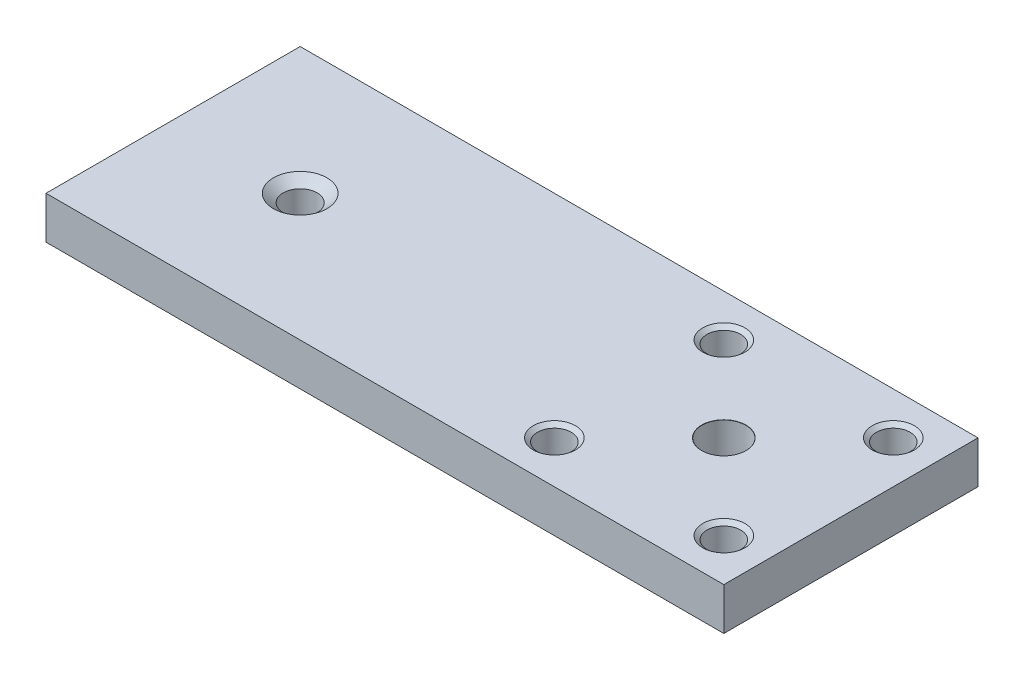
SolidWorks part; units mm, degrees
material "6061 Alloy"
ref_plane "Front" through (0, 0, 0) normal (0, 0, 1) x (1, 0, 0)
ref_plane "Top" through (0, 0, 0) normal (0, 1, 0) x (1, 0, 0)
ref_plane "Right" through (0, 0, 0) normal (1, 0, 0) x (0, 0, -1)
sketch "Sketch1" plane through (0, 0, 0) normal (0, 1, 0) x (1, 0, 0)
  line L1 (0, 0) -> (101.6, 0)
  line L2 (0, 0) -> (0, 38.1)
  line L3 (0, 38.1) -> (101.6, 38.1)
  line L4 (101.6, 0) -> (101.6, 38.1)
  dimension "D1" = 101.6
  dimension "D2" = 38.1
extrude "Boss-Extrude1" add sketch "Sketch1" along normal blind 6.35
hole_wizard "1/4-20 Tapped Hole1" positions "Sketch2" profile "Sketch3" tap size "1/4-20" standard "ANSI Inch" end condition through all
sketch "Sketch2" plane through (0, 6.35, 0) normal (0, 1, 0) x (1, 0, 0)
  line L0 (0, -50) -> (0, 50) construction
  line L1 (19.05, 19.05) -> (0, 19.05) construction
  line L3 (0, 38.1) -> (0, 0) construction
  point P0 (19.05, 19.05)
  dimension "D1" = 19.05
sketch "Sketch3" plane through (19.05, 6.35, -19.05) normal (1, 0, 0) x (0, 0, 1)
  line L0 (0, 0) -> (0, 6.35)
  line L1 (0, 6.35) -> (2.5527, 6.35)
  line L2 (2.5527, 6.35) -> (2.5527, 1.2255)
  line L3 (2.5527, 1.2255) -> (4.0132, 0)
  line L5 (4.0132, 0) -> (0, 0)
  line L6 (-2.5527, 1.2255) -> (-4.0132, 0) construction
  line L11 (0, -6.35) -> (0, 107.95) construction
  dimension "Thru Tap Drill Dia." = 5.1054
  dimension "Thru Tap Drill Depth" = 6.35
  dimension "Near C'Sink Dia." = 8.0264
  dimension "Near C'Sink Angle" = 100
cosmetic thread "Hole Thread1" parameters "D2"=6.35
hole_wizard "M6 Clearance Hole1" positions "Sketch4" profile "Sketch5" hole size "M6" standard "ANSI Metric" end condition through all
sketch "Sketch4" plane through (0, 6.35, 0) normal (0, 1, 0) x (1, 0, 0)
  line L0 (101.6, 0) -> (101.6, 38.1) construction
  line L1 (82.55, 19.05) -> (101.6, 19.05) construction
  point P0 (82.55, 19.05)
  dimension "D1" = 19.05
sketch "Sketch5" plane through (82.55, 6.35, -19.05) normal (1, 0, 0) x (0, 0, 1)
  line L0 (0, 0) -> (0, 6.35)
  line L1 (0, 6.35) -> (3.3, 6.35)
  line L2 (3.3, 6.35) -> (3.3, 0.021)
  line L3 (3.3, 0.021) -> (3.325, 0)
  line L5 (3.325, 0) -> (0, 0)
  line L6 (-3.3, 0.021) -> (-3.325, 0) construction
  line L11 (0, -6.35) -> (0, 107.95) construction
  dimension "Thru Hole Dia." = 6.6
  dimension "Thru Hole Depth" = 6.35
  dimension "Near C'Sink Dia." = 6.65
  dimension "Near C'Sink Angle" = 100
hole_wizard "#8 (0.199) Diameter Hole1" positions "Sketch6" profile "Sketch7" hole size "#8" standard "ANSI Inch" end condition through all
sketch "Sketch6" plane through (0, 6.35, 0) normal (0, 1, 0) x (1, 0, 0)
  line L0 (95.25, 38.1) -> (95.25, 31.75) construction
  line L1 (101.6, 38.1) -> (0, 38.1) construction
  line L2 (95.25, 31.75) -> (101.6, 31.75) construction
  line L3 (101.6, 0) -> (101.6, 38.1) construction
  line L5 (69.85, 31.75) -> (95.25, 31.75) construction
  line L6 (95.25, 31.75) -> (95.25, 6.35) construction
  line L7 (95.25, 6.35) -> (95.25, 0) construction
  line L8 (0, 0) -> (101.6, 0) construction
  line L10 (95.25, 6.35) -> (101.6, 6.35) construction
  point P0 (95.25, 31.75)
  point P2 (69.85, 31.75)
  point P4 (69.85, 6.35)
  point P6 (95.25, 6.35)
  dimension "D1" = 6.35
sketch "Sketch7" plane through (95.25, 6.35, -31.75) normal (1, 0, 0) x (0, 0, 1)
  line L0 (0, 0) -> (0, 6.35)
  line L1 (0, 6.35) -> (2.5273, 6.35)
  line L2 (2.5273, 6.35) -> (2.5273, 0.5328)
  line L3 (2.5273, 0.5328) -> (3.1623, 0)
  line L5 (3.1623, 0) -> (0, 0)
  line L6 (-2.5273, 0.5328) -> (-3.1623, 0) construction
  line L11 (0, -6.35) -> (0, 107.95) construction
  dimension "Thru Hole Dia." = 5.0546
  dimension "Thru Hole Depth" = 6.35
  dimension "Near C'Sink Dia." = 6.3246
  dimension "Near C'Sink Angle" = 100
